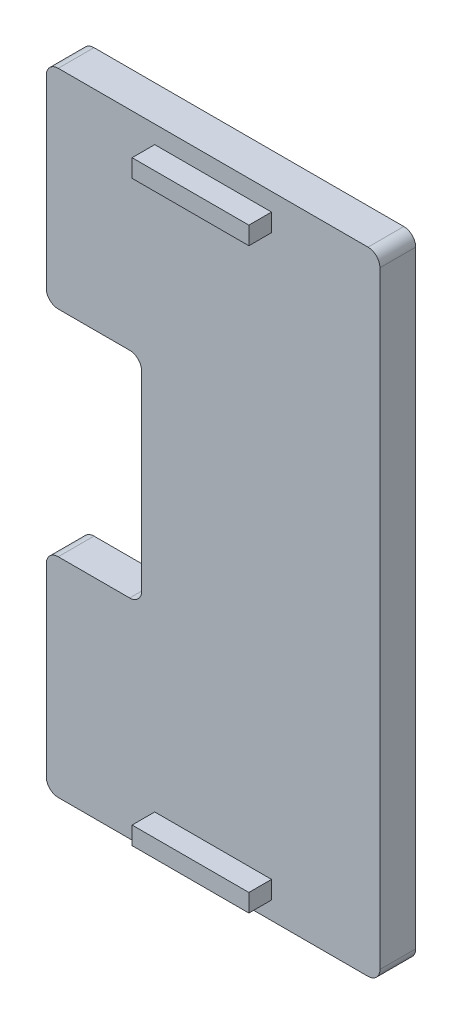
SolidWorks part; units mm, degrees
ref_plane "Front Plane" through (0, 0, 0) normal (0, 0, 1) x (1, 0, 0)
ref_plane "Top Plane" through (0, 0, 0) normal (0, 1, 0) x (1, 0, 0)
ref_plane "Right Plane" through (0, 0, 0) normal (1, 0, 0) x (0, 0, -1)
sketch "Sketch1" plane through (0, 0, 0) normal (0, 0, 1) x (1, 0, 0)
  line L0 (11, 47) -> (11, 0) construction
  line L1 (0, 0) -> (22, 0)
  line L2 (0, 0) -> (0, 47)
  line L3 (0, 47) -> (22, 47)
  line L4 (22, 0) -> (22, 47)
  line L6 (-3, -3) -> (25, -3)
  line L7 (-3, -3) -> (-3, 50)
  line L8 (-3, 50) -> (25, 50)
  line L9 (25, -3) -> (25, 50)
  line L10 (-3, -3) -> (25, 50) construction
  line L11 (-3, 50) -> (25, -3) construction
  point P7 (11, 23.5)
  dimension "D1" = 47
  dimension "D2" = 22
  dimension "D3" = 53
  dimension "D4" = 28
extrude "Boss-Extrude1" add sketch "Sketch1" along normal blind 3 contours L6 L9 L8 L7 L4 L1 L2 L3 | L1 L4 L3 L2
sketch "Sketch3" plane through (0, 0, 3) normal (0, 0, 1) x (1, 0, 0)
  line L0 (11, 50) -> (11, -3) construction
  line L1 (-3, 23.5) -> (25, 23.5) construction
  line L2 (6.1, 50) -> (15.9, 50)
  line L3 (6.1, 50) -> (6.1, 47)
  line L4 (-3, -3) -> (25, -3)
  line L5 (25, -3) -> (25, 50)
  line L6 (25, 50) -> (-3, 50)
  line L7 (-3, 50) -> (-3, -3)
  line L8 (-3, -3) -> (25, -3)
  line L9 (25, -3) -> (25, 50)
  line L10 (25, 50) -> (-3, 50)
  line L11 (-3, 50) -> (-3, -3)
  line L12 (0, 0) -> (22, 0)
  line L13 (22, 0) -> (22, 47)
  line L14 (22, 47) -> (0, 47)
  line L15 (0, 47) -> (0, 0)
  line L16 (0, 0) -> (22, 0)
  line L17 (22, 0) -> (22, 47)
  line L18 (22, 47) -> (0, 47)
  line L19 (0, 47) -> (0, 0)
  line L20 (6.1, 47) -> (15.9, 47)
  line L21 (15.9, 50) -> (15.9, 47)
  line L22 (6.1, 0) -> (15.9, 0)
  line L23 (15.9, -3) -> (15.9, 0)
  line L24 (6.1, -3) -> (15.9, -3)
  line L25 (6.1, -3) -> (6.1, 0)
  line L26 (6.1, -1.5) -> (15.9, -1.5)
  line L27 (6.1, 50) -> (15.9, 50)
  line L28 (6.1, 50) -> (6.1, 48.5)
  line L29 (6.1, 48.5) -> (15.9, 48.5)
  line L30 (15.9, 50) -> (15.9, 48.5)
  dimension "D3" = 4.9
  dimension "D4" = 9.8
  dimension "D1" = 0
  dimension "D2" = 0
extrude "Boss-Extrude2" add sketch "Sketch3" along normal blind 1.9 contours L29 L3 L18 L21 | L25 L26 L23 L16
sketch "Sketch4" plane through (0, 0, 0) normal (0, 0, -1) x (-1, 0, 0)
  line L0 (-25, 23.5) -> (3, 23.5) construction
  line L1 (-25, -3) -> (-25, 50) construction
  line L2 (3, -3) -> (3, 50) construction
  line L4 (11, 14.5) -> (-5, 14.5)
  line L5 (11, 14.5) -> (11, 32.5)
  line L6 (11, 32.5) -> (-5, 32.5)
  line L7 (-5, 14.5) -> (-5, 32.5)
  line L8 (11, 14.5) -> (-5, 32.5) construction
  line L9 (11, 32.5) -> (-5, 14.5) construction
  dimension "D1" = 16
  dimension "D2" = 18
extrude "Cut-Extrude1" cut sketch "Sketch4" against normal through all
fillet "Fillet1" radius 1 8 edges at (-3, -3, 1.5) (25, -3, 1.5) (25, 50, 1.5) (-3, 50, 1.5) (-3, 14.5, 1.5) (5, 14.5, 1.5) (-3, 32.5, 1.5) (5, 32.5, 1.5)
